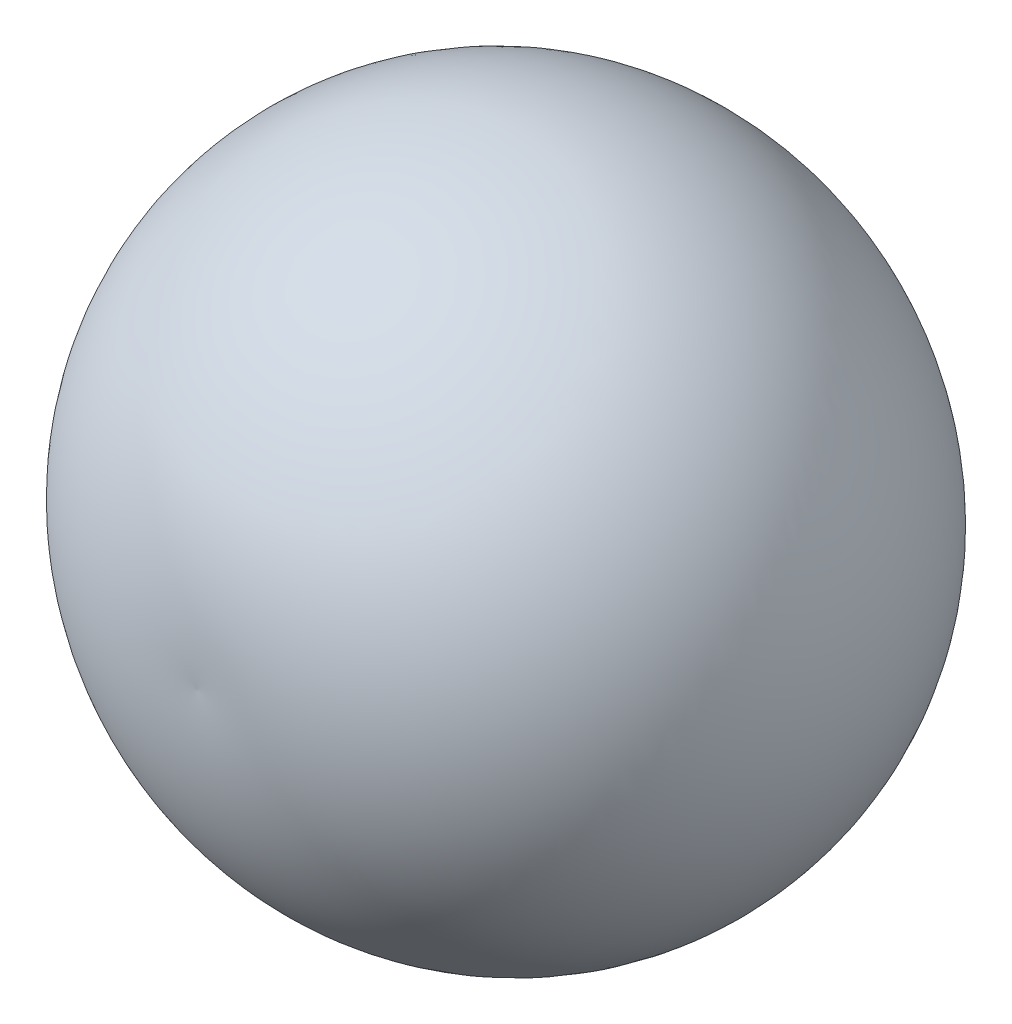
SolidWorks part; units mm, degrees
ref_plane "Front Plane" through (0, 0, 0) normal (0, 0, 1) x (1, 0, 0)
ref_plane "Top Plane" through (0, 0, 0) normal (0, 1, 0) x (1, 0, 0)
ref_plane "Right Plane" through (0, 0, 0) normal (1, 0, 0) x (0, 0, -1)
sketch "Sketch1" plane through (0, 0, 0) normal (0, 1, 0) x (1, 0, 0)
  line L0 (-0.5436, 7.4803) -> (-0.5436, -7.4803) construction
  line L1 (-0.5436, 7.4803) -> (-0.5436, -7.4803)
  arc A0 (-0.5436, 7.4803) -> (-0.5436, -7.4803) centre (0, 0) cw
  dimension "D1" = 7.5
revolve "Revolve1" add sketch "Sketch1" angle 360 about L0
